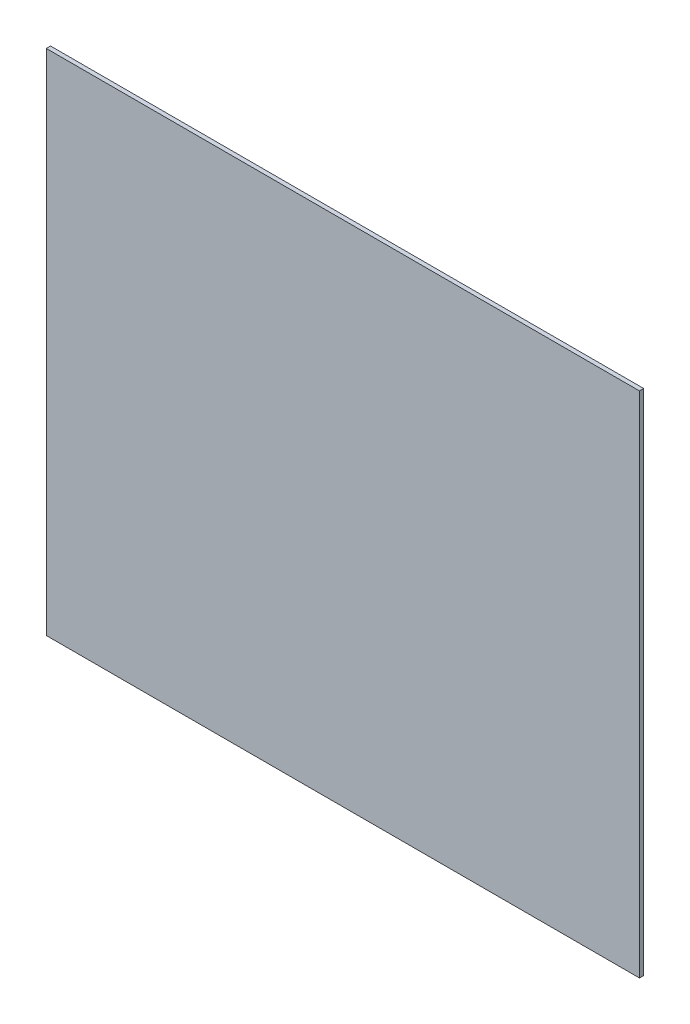
SolidWorks part; units mm, degrees
material "3003 Alloy"
ref_plane "Front Plane" through (0, 0, 0) normal (0, 0, 1) x (1, 0, 0)
ref_plane "Top Plane" through (0, 0, 0) normal (0, 1, 0) x (1, 0, 0)
ref_plane "Right Plane" through (0, 0, 0) normal (1, 0, 0) x (0, 0, -1)
sketch "Sketch1" plane through (0, 0, 0) normal (0, 0, 1) x (1, 0, 0)
  line L1 (140, -120) -> (-140, -120)
  line L2 (140, -120) -> (140, 120)
  line L3 (140, 120) -> (-140, 120)
  line L4 (-140, -120) -> (-140, 120)
  line L5 (140, -120) -> (-140, 120) construction
  line L6 (140, 120) -> (-140, -120) construction
  point P0 (0, 0)
  dimension "D1" = 280
  dimension "D2" = 240
extrude "Boss-Extrude1" add sketch "Sketch1" along normal blind 2
